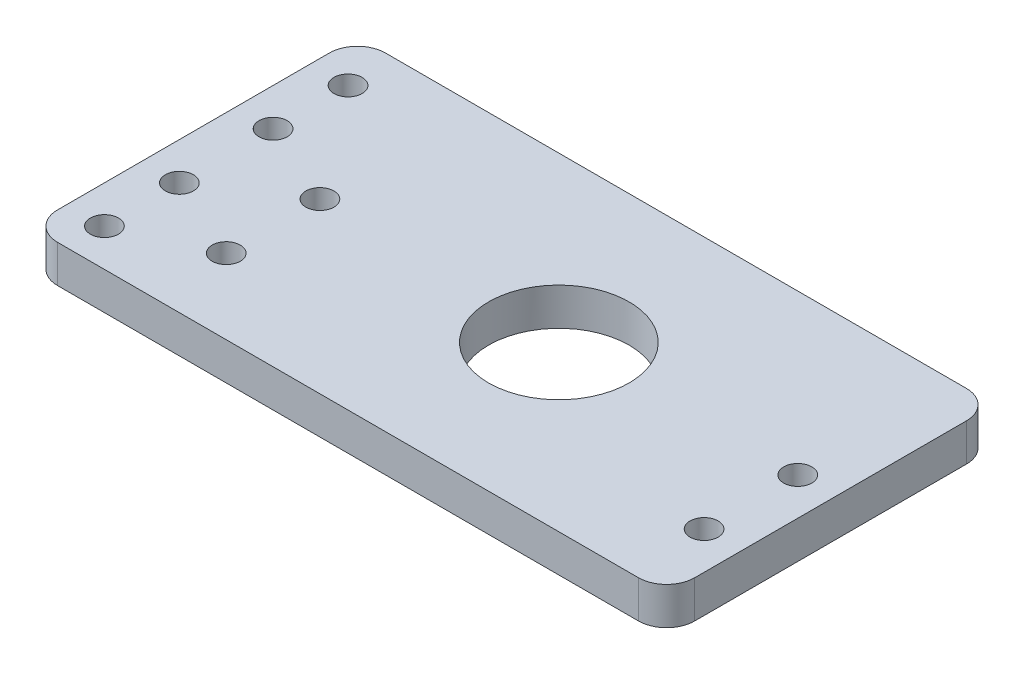
SolidWorks part; units mm, degrees
material "Thornel Mat VMA"
ref_plane "前视基准面" through (0, 0, 0) normal (0, 0, 1) x (1, 0, 0)
ref_plane "上视基准面" through (0, 0, 0) normal (0, 1, 0) x (1, 0, 0)
ref_plane "右视基准面" through (0, 0, 0) normal (1, 0, 0) x (0, 0, -1)
other "Configuration Table"
sketch "草图1" plane through (0, 0, 0) normal (0, 1, 0) x (1, 0, 0)
  line L1 (-34, -17.5) -> (34, -17.5)
  line L2 (-34, -17.5) -> (-34, 17.5)
  line L3 (-34, 17.5) -> (34, 17.5)
  line L4 (34, -17.5) -> (34, 17.5)
  line L5 (-34, -17.5) -> (34, 17.5) construction
  line L6 (-34, 17.5) -> (34, -17.5) construction
  circle A0 centre (-30, 12.5) radius 1.5
  circle A1 centre (-30, 4.5) radius 1.5
  circle A2 centre (-30, -5.5) radius 1.5
  circle A3 centre (-30, -13.5) radius 1.5
  point P0 (0, 0)
  dimension "D3" = 3
  dimension "D4" = 3
  dimension "D5" = 8
  dimension "D7" = 4
  dimension "D8" = 3
  dimension "D9" = 3
  dimension "D10" = 8
  dimension "D11" = 4
  dimension "D12" = 4
  dimension "D13" = 10
  dimension "D14" = 5
  dimension "D6" = 4
  dimension "D1" = 68
  dimension "D2" = 35
extrude "凸台-拉伸1" add sketch "草图1" along normal blind 4
fillet "圆角1" radius 3 4 edges at (34, 2, 17.5) (34, 2, -17.5) (-34, 2, 17.5) (-34, 2, -17.5)
sketch "草图2" plane through (0, 4, 0) normal (0, 1, 0) x (1, 0, 0)
  line L0 (-34, 14.5) -> (-34, -14.5) construction
  line L1 (34, -14.5) -> (34, 14.5) construction
  line L2 (-31, -17.5) -> (31, -17.5) construction
  line L3 (31, 17.5) -> (-31, 17.5) construction
  circle A0 centre (-21, 0.5) radius 1.5
  circle A1 centre (30, 0.5) radius 1.5
  circle A2 centre (-21, -9.5) radius 1.5
  circle A3 centre (30, -9.5) radius 1.5
  circle A4 centre (5, 0) radius 7.5
  dimension "D1" = 3
  dimension "D2" = 3
  dimension "D3" = 3
  dimension "D4" = 3
  dimension "D5" = 13
  dimension "D6" = 4
  dimension "D7" = 8
  dimension "D8" = 8
  dimension "D9" = 51
  dimension "D10" = 17
  dimension "D12" = 13
  dimension "D13" = 15
  dimension "D14" = 5
  dimension "D11" = 17
  dimension "D15" = 17.5
extrude "切除-拉伸1" cut sketch "草图2" against normal blind 10
